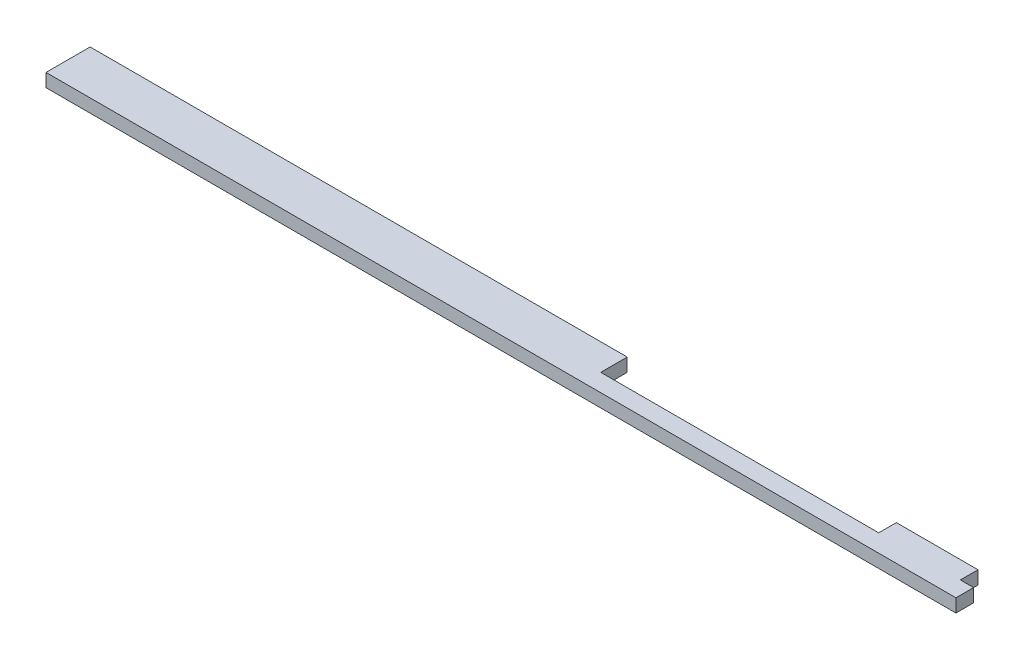
SolidWorks part; units mm, degrees
ref_plane "Front Plane" through (0, 0, 0) normal (0, 0, 1) x (1, 0, 0)
ref_plane "Top Plane" through (0, 0, 0) normal (0, 1, 0) x (1, 0, 0)
ref_plane "Right Plane" through (0, 0, 0) normal (1, 0, 0) x (0, 0, -1)
sketch "Sketch1" plane through (0, 0, 0) normal (0, 1, 0) x (1, 0, 0)
  line L0 (0, 5) -> (0, -5) construction
  line L1 (-103.12, 5) -> (103.12, 5)
  line L2 (-103.12, 5) -> (-103.12, -5)
  line L3 (-103.12, -5) -> (103.12, -5)
  line L4 (103.12, 5) -> (103.12, -5)
  dimension "D1" = 206.24
  dimension "D2" = 10
extrude "Boss-Extrude1" add sketch "Sketch1" along normal blind 3
sketch "Sketch2" plane through (0, 3, 0) normal (0, 1, 0) x (1, 0, 0)
  line L1 (103.12, 5) -> (18.62, 5)
  line L2 (81.62, 3) -> (81.62, -1)
  line L3 (81.62, -1) -> (18.62, -1)
  line L4 (18.62, 5) -> (18.62, -1)
  line L6 (103.12, 5) -> (-103.12, 5) construction
  line L9 (103.12, 5) -> (103.12, -1)
  line L10 (103.12, -1) -> (100.12, -1)
  line L11 (100.12, 3) -> (100.12, -1)
  line L12 (100.12, 3) -> (81.62, 3)
  point P4 (0, 0)
  point P5 (96.5858, 5)
  point P6 (0, 0)
  point P7 (102.8776, 5)
  point P19 (98.0338, 5)
  point P20 (0, 0)
  dimension "D1" = 21.5
  dimension "D2" = 3
  dimension "D3" = 84.5
  dimension "D4" = 6
  dimension "D5" = 2
extrude "Cut-Extrude1" cut sketch "Sketch2" against normal through all
